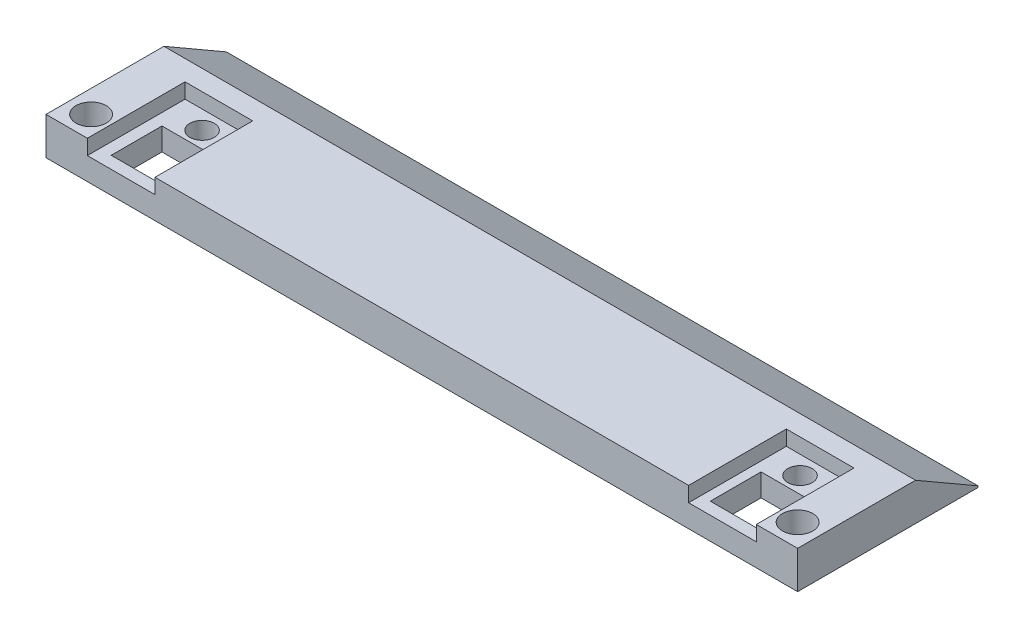
SolidWorks part; units mm, degrees
ref_plane "Alzado" through (0, 0, 0) normal (0, 0, 1) x (1, 0, 0)
ref_plane "Planta" through (0, 0, 0) normal (0, 1, 0) x (1, 0, 0)
ref_plane "Vista lateral" through (0, 0, 0) normal (1, 0, 0) x (0, 0, -1)
sketch "Croquis1" plane through (0, 0, 0) normal (0, 1, 0) x (1, 0, 0)
  line L0 (-44, -12) -> (-44, 0)
  line L1 (-50, 12) -> (50, 12)
  line L2 (-50, 12) -> (-50, -12)
  line L3 (-50, -12) -> (50, -12)
  line L4 (50, 12) -> (50, -12)
  line L5 (-50, 12) -> (50, -12) construction
  line L6 (-50, -12) -> (50, 12) construction
  line L7 (-44, 0) -> (-36, 0)
  line L8 (-36, 0) -> (-36, -12)
  line L9 (0, 0) -> (0, -6.9349) construction
  line L10 (36, 0) -> (36, -12)
  line L12 (44, -12) -> (44, 0)
  line L13 (-42.9486, -3.6227) -> (-37.0514, -3.6227)
  line L14 (-42.9486, -3.6227) -> (-42.9486, -10.3773)
  line L15 (-42.9486, -10.3773) -> (-37.0514, -10.3773)
  line L16 (-37.0514, -3.6227) -> (-37.0514, -10.3773)
  line L17 (-42.9486, -3.6227) -> (-37.0514, -10.3773) construction
  line L18 (-42.9486, -10.3773) -> (-37.0514, -3.6227) construction
  line L19 (36.7611, -3.6227) -> (43.2389, -3.6227)
  line L20 (36.7611, -3.6227) -> (36.7611, -10.3773)
  line L21 (36.7611, -10.3773) -> (43.2389, -10.3773)
  line L22 (43.2389, -3.6227) -> (43.2389, -10.3773)
  line L23 (36.7611, -3.6227) -> (43.2389, -10.3773) construction
  line L24 (36.7611, -10.3773) -> (43.2389, -3.6227) construction
  circle A0 centre (-47, -9) radius 2.0175
  circle A1 centre (-40, -7) radius 2.25
  circle A2 centre (40, -7) radius 2.25
  circle A3 centre (47, -9) radius 2.0175
  point P0 (0, 0)
  dimension "D9" = 4.5
  dimension "D1" = 24
  dimension "D2" = 100
  dimension "D3" = 3
  dimension "D4" = 3
  dimension "D5" = 6
  dimension "D6" = 8
  dimension "D7" = 12
  dimension "D8" = 2
extrude "Saliente-Extruir1" add sketch "Croquis1" along normal blind 5
sketch "Croquis2" plane through (0, 5, 0) normal (0, 1, 0) x (1, 0, 0)
  line L0 (-50, -12) -> (50, -12) construction
  line L5 (0, 0) -> (0, -5.1087) construction
  line L13 (-35.5, -12) -> (-35.5, 1)
  line L14 (-35.5, 1) -> (-44.5, 1)
  line L15 (-44.5, -12) -> (-44.5, 1)
  line L16 (-35.5, -12) -> (-44.5, -12)
  line L17 (44.5, -12) -> (44.5, 1)
  line L18 (35.5, 1) -> (44.5, 1)
  line L19 (35.5, -12) -> (35.5, 1)
  line L20 (35.5, -12) -> (44.5, -12)
  circle A4 centre (-40, -7) radius 2.5
  circle A5 centre (40, -7) radius 2.5
  point P0 (-40, -7)
  point P15 (40, -7)
  point P18 (-35.5, 0)
  point P19 (44.5, 0)
  point P20 (35.5, 0)
  point P21 (-44.5, 0)
  point P22 (40, -7)
  dimension "D4" = 5
  dimension "D1" = 13
  dimension "D2" = 4.5
extrude "Cortar-Extruir1" cut sketch "Croquis2" against normal blind 2
sketch "Croquis3" plane through (-50, 0, 0) normal (-1, 0, 0) x (0, 0, 1)
  line L0 (-12, 0) -> (-12, 0.2)
  line L1 (-12, 5) -> (-12, 0) construction
  line L2 (-12, 0.2) -> (-6.1009, 3.6058)
  line L3 (-12, 0) -> (-5.7905, 0)
  line L4 (-12, 0) -> (12, 0) construction
  line L5 (-6.1009, 3.6058) -> (-3.0399, 5.3731)
  line L6 (-3.0399, 5.3731) -> (-12.7572, 5.3731)
  line L7 (-12.7572, 5.3731) -> (-12.7572, 0.2)
  line L8 (-12.7572, 0.2) -> (-12, 0.2)
  line M10 (12, 5) -> (-12, 5)
  line M11 (-12, 5) -> (-12, 0)
  dimension "D1" = 0.2
  dimension "D2" = 30
extrude "Cortar-Extruir5" cut sketch "Croquis3" against normal blind 141 contours L2 L5 M10 M11 | L7 L8 L5 L6 M11 M10
sketch "Croquis5" plane through (0, 3, 0) normal (0, 1, 0) x (1, 0, 0)
  line L0 (0, 0) -> (0, -4.2422) construction
  circle A0 centre (39.7784, -1.4593) radius 1.6268
  circle A1 centre (-39.7784, -1.4593) radius 1.6268
extrude "Cortar-Extruir6" cut sketch "Croquis5" along normal blind 21 and the other way blind 26
